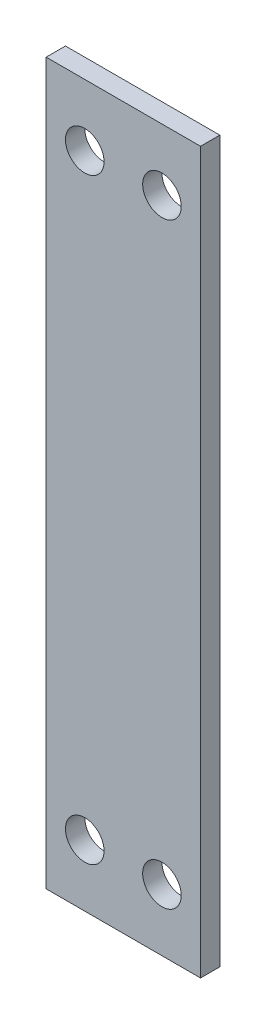
SolidWorks part; units mm, degrees
ref_plane "Front Plane" through (0, 0, 0) normal (0, 0, 1) x (1, 0, 0)
ref_plane "Top Plane" through (0, 0, 0) normal (0, 1, 0) x (1, 0, 0)
ref_plane "Right Plane" through (0, 0, 0) normal (1, 0, 0) x (0, 0, -1)
sketch "Sketch1" plane through (0, 0, 0) normal (0, 0, 1) x (1, 0, 0)
  line L0 (0, 9.9974) -> (38.1, 9.9974) construction
  line L1 (0, 0) -> (38.1, 0)
  line L2 (0, 0) -> (0, 177.8)
  line L3 (0, 177.8) -> (38.1, 177.8)
  line L4 (38.1, 0) -> (38.1, 177.8)
  line L5 (19.05, 15.24) -> (38.1, 15.24) construction
  line L6 (19.05, 225.3621) -> (38.1, 225.3621) construction
  circle A0 centre (9.525, 15.24) radius 4.7625
  circle A1 centre (28.575, 15.24) radius 4.7625
  circle A2 centre (9.525, 162.56) radius 4.7625
  circle A3 centre (28.575, 162.56) radius 4.7625
  point P13 (19.05, 9.9974)
  point P14 (28.575, 15.24)
  point P21 (19.05, 177.8)
  point P22 (28.575, 225.3621)
  dimension "D4" = 9.525
  dimension "D6" = 9.525
  dimension "D1" = 177.8
  dimension "D2" = 38.1
  dimension "D3" = 19.05
  dimension "D5" = 15.24
  dimension "D7" = 19.05
  dimension "D8" = 15.24
extrude "Boss-Extrude1" add sketch "Sketch1" along normal blind 4.7625
